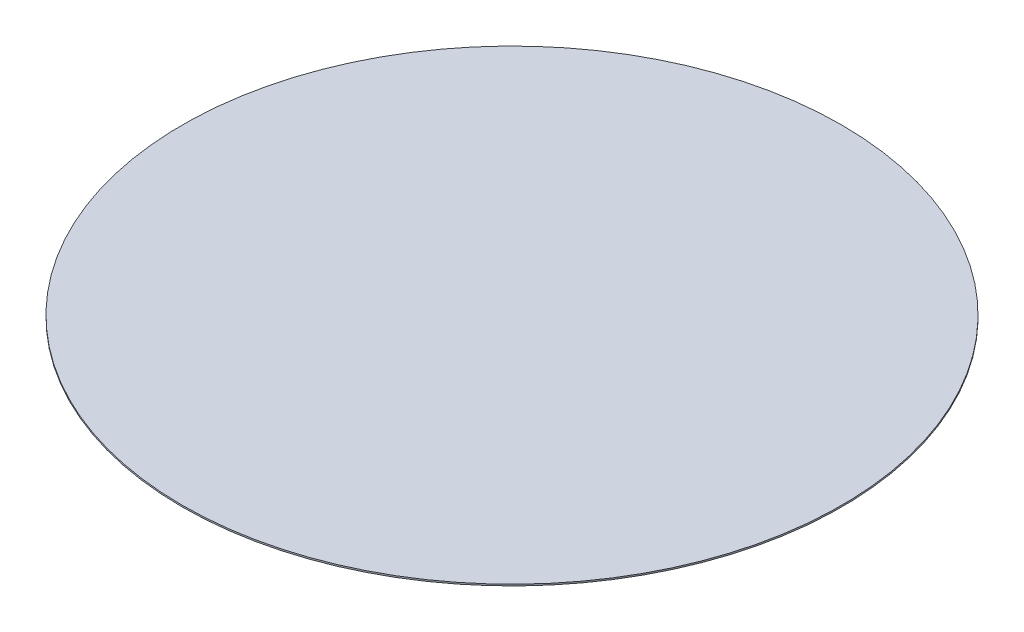
SolidWorks part; units mm, degrees
ref_plane "Front Plane" through (0, 0, 0) normal (0, 0, 1) x (1, 0, 0)
ref_plane "Top Plane" through (0, 0, 0) normal (0, 1, 0) x (1, 0, 0)
ref_plane "Right Plane" through (0, 0, 0) normal (1, 0, 0) x (0, 0, -1)
sketch "Sketch1" plane through (0, 0, 0) normal (0, 1, 0) x (1, 0, 0)
  circle A0 centre (0, 0) radius 550.164
extrude "Boss-Extrude1" add sketch "Sketch1" along normal blind 2.54
